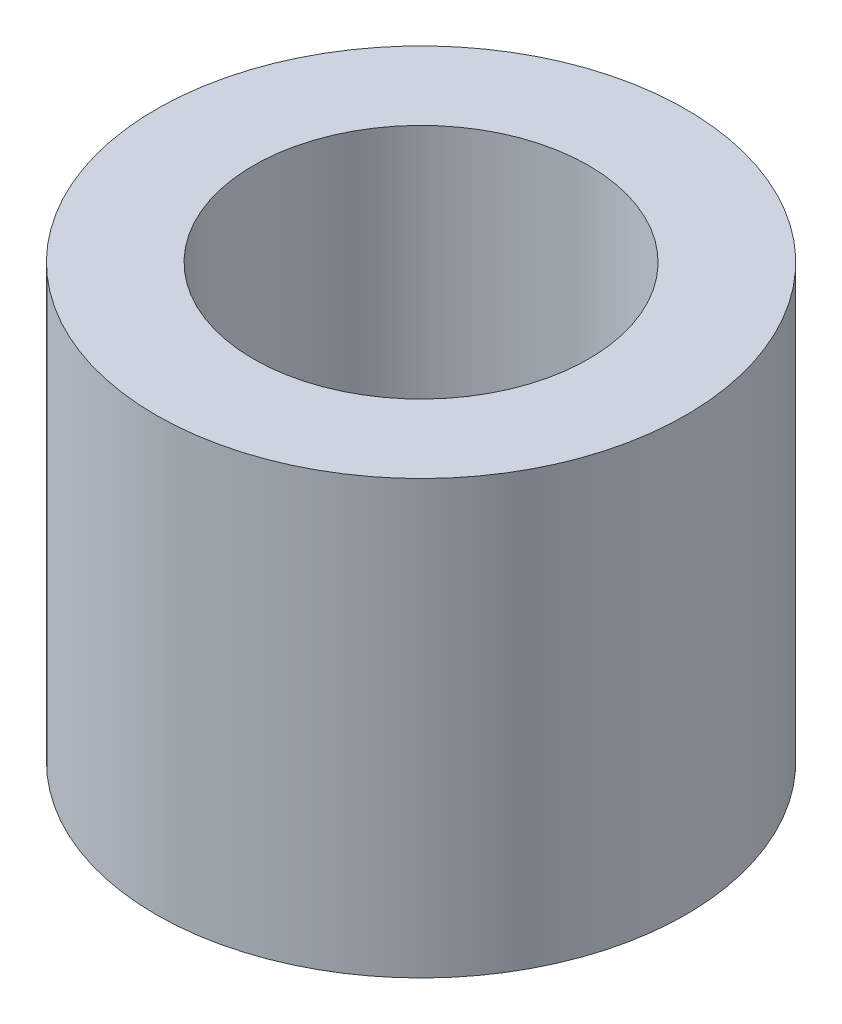
SolidWorks part; units mm, degrees
ref_plane "Front Plane" through (0, 0, 0) normal (0, 0, 1) x (1, 0, 0)
ref_plane "Top Plane" through (0, 0, 0) normal (0, 1, 0) x (1, 0, 0)
ref_plane "Right Plane" through (0, 0, 0) normal (1, 0, 0) x (0, 0, -1)
sketch "Sketch2" plane through (0, 0, 0) normal (0, 1, 0) x (1, 0, 0)
  line L0 (-9.7681, 0) -> (10.1509, 0) construction
  circle A0 centre (0, 0) radius 2.45
  point P4 (0, 0)
  dimension "D1" = 4.9
extrude "Boss-Extrude1" add sketch "Sketch2" along normal blind 4
sketch "Sketch4" plane through (0, 4, 0) normal (0, 1, 0) x (1, 0, 0)
  circle A0 centre (0, 0) radius 1.55
  point P2 (0, 0)
  dimension "D1" = 3.1
extrude "Cut-Extrude1" cut sketch "Sketch4" against normal blind 3
